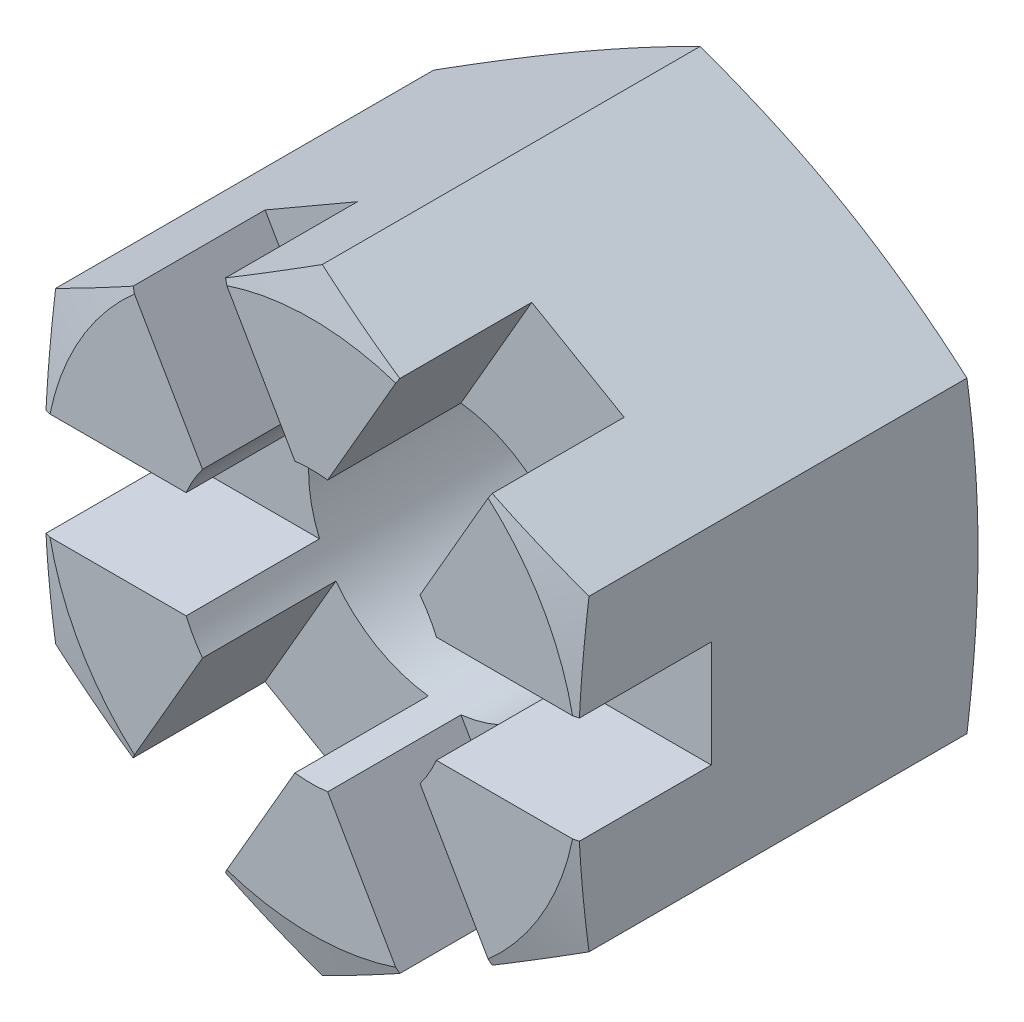
SolidWorks part; units mm, degrees
ref_plane "Přední rovina" through (0, 0, 0) normal (0, 0, 1) x (1, 0, 0)
ref_plane "Vrchní rovina" through (0, 0, 0) normal (0, 1, 0) x (1, 0, 0)
ref_plane "Pravá rovina" through (0, 0, 0) normal (1, 0, 0) x (0, 0, -1)
sketch "Skica1" plane through (0, 0, 0) normal (0, 0, 1) x (1, 0, 0)
  line L1 (5, -2.8868) -> (5, 2.8868)
  line L2 (5, 2.8868) -> (0, 5.7735)
  line L3 (0, 5.7735) -> (-5, 2.8868)
  line L4 (-5, 2.8868) -> (-5, -2.8868)
  line L5 (-5, -2.8868) -> (0, -5.7735)
  line L6 (0, -5.7735) -> (5, -2.8868)
  circle A0 centre (0, 0) radius 5 construction
  dimension "s" = 10
extrude "Vysunout1" add sketch "Skica1" along normal blind 7.5
sketch "Skica3" plane through (0, 0, 0) normal (0, 1, 0) x (1, 0, 0)
  line L0 (-5, 0) -> (-18.9952, 0)
  line L1 (-18.9952, 0) -> (-18.9952, -7.5)
  line L2 (-18.9952, -7.5) -> (-5, -7.5)
  line L3 (-5, 0) -> (-18.9952, -3.75)
  line L4 (-18.9952, -3.75) -> (-5, -7.5)
  line L5 (0, 0) -> (0, -7.5) construction
  dimension "D1" = 15
revolve "Odebrat otočením1" cut sketch "Skica3" angle 360 about L5
sketch "Skica7" plane through (0, 0, 7.5) normal (0, 0, 1) x (1, 0, 0)
  circle A0 centre (0, 0) radius 4
  dimension "D" = 8
extrude "Vysunout2" add sketch "Skica7" along normal blind 2.5
sketch "Skica4" plane through (0, 0, 0) normal (0, 0, -1) x (-1, 0, 0)
  circle A0 centre (0, 0) radius 2.55
  dimension "D1" = 5.1
extrude "Odebrat vysunutím1" cut sketch "Skica4" against normal through all
cosmetic thread "Kosmetický závit1" parameters "M"=6
sketch "Skica5" plane through (0, 0, 7.5) normal (0, 0, 1) x (1, 0, 0)
  line L0 (0, 0) -> (5, 0) construction
  line L1 (-5, 1) -> (5, 1)
  line L2 (-5, 1) -> (-5, -1)
  line L3 (-5, -1) -> (5, -1)
  line L4 (5, 1) -> (5, -1)
  line L5 (5, 0) -> (5, 2.8868) construction
  line L6 (-5, 2.8868) -> (-5, 0) construction
  dimension "n" = 2
extrude "Odebrat vysunutím2" cut sketch "Skica5" against normal blind 2.5
pattern_circular "Kruhové pole1" count 3 over 360 about axis through (0, 0, 0) along (0, 0, 1) of "Odebrat vysunutím2"
chamfer "Zkosit1" distance 0.6 angle 30 1 edges at (-2.55, 0, 0)
fillet "Zaoblit1" radius 1
sketch "Skica9" plane through (0, 0, 50) normal (0, 0, 1) x (1, 0, 0)
  line L0 (0, 0) -> (-37.5, 0) construction
  line L1 (-37.5, 4.5) -> (37.5, 4.5)
  line L2 (-37.5, 4.5) -> (-37.5, -4.5)
  line L3 (-37.5, -4.5) -> (37.5, -4.5)
  line L4 (37.5, 4.5) -> (37.5, -4.5)
  line L5 (-37.5, 21.6506) -> (-37.5, 0) construction
  line L6 (37.5, 0) -> (37.5, 21.6506) construction
  dimension "D1" = 2
extrude "Odebrat vysunutím3" cut sketch "Skica9" against normal blind 2.5
pattern_circular "Kruhové pole2" count 3 every 60
equation "\"D1@Skica4\" = \"M@Kosmetický závit1\"*0.85"
equation "\"D1@Zkosit1\" = \"M@Kosmetický závit1\"*0.1"
equation "\"D1@Vysunout2\" = \"h-m@Odebrat vysunutím2\""
equation "\"D1@Skica9\" = \"n@Skica5\""
equation "\"D1@Zaoblit1\" = (\"s@Skica1\"-\"D@Skica7\")/2"
